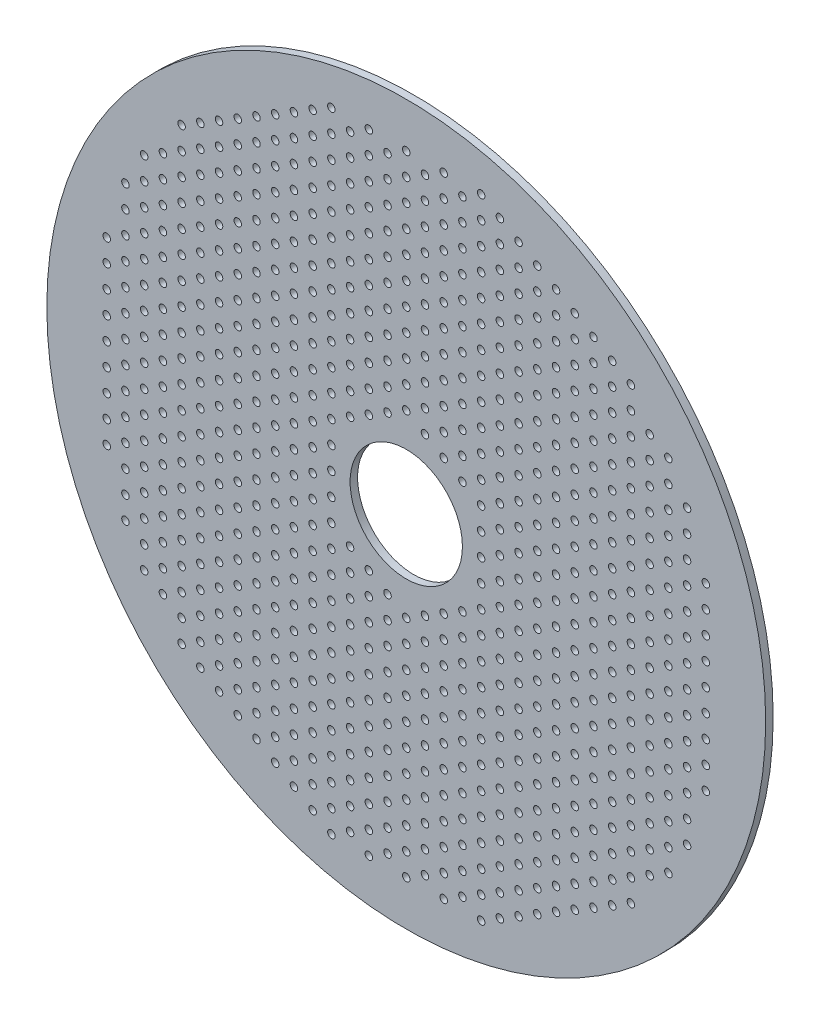
SolidWorks part; units mm, degrees
ref_plane "前视基准面" through (0, 0, 0) normal (0, 0, 1) x (1, 0, 0)
ref_plane "上视基准面" through (0, 0, 0) normal (0, 1, 0) x (1, 0, 0)
ref_plane "右视基准面" through (0, 0, 0) normal (1, 0, 0) x (0, 0, -1)
other "Configuration Table"
sketch "草图1" plane through (0, 0, 0) normal (0, 0, 1) x (1, 0, 0)
  line L0 (972.5716, 0) -> (-1078.2776, 0) construction
  line L1 (-52.853, -768.3582) -> (-52.853, 768.3582) construction
  line L2 (-452.853, 0) -> (-452.853, -30) construction
  line L3 (-202.853, 0) -> (-202.853, -30) construction
  line L4 (97.147, 0) -> (97.147, -30) construction
  line L5 (347.147, 0) -> (347.147, -30) construction
  circle A2 centre (-152.853, 0) radius 5
  circle A3 centre (-202.853, 0) radius 5
  circle A4 centre (-252.853, 0) radius 5
  circle A5 centre (-302.853, 0) radius 5
  circle A6 centre (-352.853, 0) radius 5
  circle A7 centre (-402.853, 0) radius 5
  circle A8 centre (-452.853, 0) radius 5
  circle A9 centre (-452.853, -30) radius 5
  circle A10 centre (-452.853, -60) radius 5
  circle A11 centre (-452.853, -90) radius 5
  circle A12 centre (-452.853, -120) radius 5
  circle A13 centre (-402.853, -30) radius 5
  circle A14 centre (-402.853, -60) radius 5
  circle A15 centre (-402.853, -90) radius 5
  circle A16 centre (-402.853, -120) radius 5
  circle A17 centre (-402.853, -150) radius 5
  circle A18 centre (-402.853, -180) radius 5
  circle A19 centre (-402.853, -210) radius 5
  circle A20 centre (-402.853, -240) radius 5
  circle A21 centre (-352.853, -30) radius 5
  circle A22 centre (-352.853, -60) radius 5
  circle A23 centre (-352.853, -90) radius 5
  circle A24 centre (-352.853, -120) radius 5
  circle A25 centre (-352.853, -150) radius 5
  circle A26 centre (-352.853, -180) radius 5
  circle A27 centre (-352.853, -210) radius 5
  circle A28 centre (-352.853, -240) radius 5
  circle A29 centre (-352.853, -270) radius 5
  circle A30 centre (-352.853, -300) radius 5
  circle A31 centre (-302.853, -30) radius 5
  circle A32 centre (-302.853, -60) radius 5
  circle A33 centre (-302.853, -90) radius 5
  circle A34 centre (-302.853, -120) radius 5
  circle A35 centre (-302.853, -150) radius 5
  circle A36 centre (-302.853, -180) radius 5
  circle A37 centre (-302.853, -210) radius 5
  circle A38 centre (-302.853, -240) radius 5
  circle A39 centre (-302.853, -270) radius 5
  circle A40 centre (-302.853, -300) radius 5
  circle A41 centre (-302.853, -330) radius 5
  circle A42 centre (-252.853, -30) radius 5
  circle A43 centre (-252.853, -60) radius 5
  circle A44 centre (-252.853, -90) radius 5
  circle A45 centre (-252.853, -120) radius 5
  circle A46 centre (-252.853, -150) radius 5
  circle A47 centre (-252.853, -180) radius 5
  circle A48 centre (-252.853, -210) radius 5
  circle A49 centre (-252.853, -240) radius 5
  circle A50 centre (-252.853, -270) radius 5
  circle A51 centre (-252.853, -300) radius 5
  circle A52 centre (-252.853, -330) radius 5
  circle A53 centre (-252.853, -360) radius 5
  circle A54 centre (-202.853, -30) radius 5
  circle A55 centre (-202.853, -60) radius 5
  circle A56 centre (-202.853, -90) radius 5
  circle A57 centre (-202.853, -120) radius 5
  circle A58 centre (-202.853, -150) radius 5
  circle A59 centre (-202.853, -180) radius 5
  circle A60 centre (-202.853, -210) radius 5
  circle A61 centre (-202.853, -240) radius 5
  circle A62 centre (-202.853, -270) radius 5
  circle A63 centre (-202.853, -300) radius 5
  circle A64 centre (-202.853, -330) radius 5
  circle A65 centre (-202.853, -360) radius 5
  circle A66 centre (-202.853, -390) radius 5
  circle A67 centre (-152.853, -30) radius 5
  circle A68 centre (-152.853, -60) radius 5
  circle A69 centre (-152.853, -90) radius 5
  circle A70 centre (-152.853, -120) radius 5
  circle A71 centre (-152.853, -150) radius 5
  circle A72 centre (-152.853, -180) radius 5
  circle A73 centre (-152.853, -210) radius 5
  circle A74 centre (-152.853, -240) radius 5
  circle A75 centre (-152.853, -270) radius 5
  circle A76 centre (-152.853, -300) radius 5
  circle A77 centre (-152.853, -330) radius 5
  circle A78 centre (-152.853, -360) radius 5
  circle A79 centre (-152.853, -390) radius 5
  circle A80 centre (-152.853, -420) radius 5
  circle A81 centre (-427.853, -15) radius 5
  circle A82 centre (-377.853, -15) radius 5
  circle A83 centre (-327.853, -15) radius 5
  circle A84 centre (-277.853, -15) radius 5
  circle A85 centre (-227.853, -15) radius 5
  circle A86 centre (-177.853, -15) radius 5
  circle A87 centre (-377.853, -45) radius 5
  circle A88 centre (-327.853, -45) radius 5
  circle A89 centre (-277.853, -45) radius 5
  circle A90 centre (-227.853, -45) radius 5
  circle A91 centre (-177.853, -45) radius 5
  circle A92 centre (-377.853, -75) radius 5
  circle A93 centre (-327.853, -75) radius 5
  circle A94 centre (-277.853, -75) radius 5
  circle A95 centre (-227.853, -75) radius 5
  circle A96 centre (-177.853, -75) radius 5
  circle A97 centre (-377.853, -105) radius 5
  circle A98 centre (-327.853, -105) radius 5
  circle A99 centre (-277.853, -105) radius 5
  circle A100 centre (-227.853, -105) radius 5
  circle A101 centre (-177.853, -105) radius 5
  circle A102 centre (-377.853, -135) radius 5
  circle A103 centre (-327.853, -135) radius 5
  circle A104 centre (-277.853, -135) radius 5
  circle A105 centre (-227.853, -135) radius 5
  circle A106 centre (-177.853, -135) radius 5
  circle A107 centre (-377.853, -165) radius 5
  circle A108 centre (-327.853, -165) radius 5
  circle A109 centre (-277.853, -165) radius 5
  circle A110 centre (-227.853, -165) radius 5
  circle A111 centre (-177.853, -165) radius 5
  circle A112 centre (-377.853, -195) radius 5
  circle A113 centre (-327.853, -195) radius 5
  circle A114 centre (-277.853, -195) radius 5
  circle A115 centre (-227.853, -195) radius 5
  circle A116 centre (-177.853, -195) radius 5
  circle A117 centre (-377.853, -225) radius 5
  circle A118 centre (-327.853, -225) radius 5
  circle A119 centre (-277.853, -225) radius 5
  circle A120 centre (-227.853, -225) radius 5
  circle A121 centre (-177.853, -225) radius 5
  circle A122 centre (-377.853, -255) radius 5
  circle A123 centre (-327.853, -255) radius 5
  circle A124 centre (-277.853, -255) radius 5
  circle A125 centre (-227.853, -255) radius 5
  circle A126 centre (-177.853, -255) radius 5
  circle A128 centre (-327.853, -285) radius 5
  circle A129 centre (-277.853, -285) radius 5
  circle A130 centre (-227.853, -285) radius 5
  circle A131 centre (-177.853, -285) radius 5
  circle A133 centre (-327.853, -315) radius 5
  circle A134 centre (-277.853, -315) radius 5
  circle A135 centre (-227.853, -315) radius 5
  circle A136 centre (-177.853, -315) radius 5
  circle A139 centre (-277.853, -345) radius 5
  circle A140 centre (-227.853, -345) radius 5
  circle A141 centre (-177.853, -345) radius 5
  circle A145 centre (-227.853, -375) radius 5
  circle A146 centre (-177.853, -375) radius 5
  circle A151 centre (-177.853, -405) radius 5
  circle A167 centre (-427.853, -45) radius 5
  circle A168 centre (-427.853, -75) radius 5
  circle A169 centre (-427.853, -105) radius 5
  circle A170 centre (-427.853, -135) radius 5
  circle A171 centre (-427.853, -165) radius 5
  circle A172 centre (-427.853, -195) radius 5
  circle A183 centre (-427.853, -255) radius 5 [skipped]
  circle A184 centre (-427.853, -285) radius 5 [skipped]
  circle A185 centre (-427.853, -315) radius 5 [skipped]
  circle A186 centre (-427.853, -345) radius 5 [skipped]
  circle A187 centre (-427.853, -375) radius 5 [skipped]
  circle A188 centre (-427.853, -405) radius 5 [skipped]
  circle A189 centre (-427.853, -435) radius 5 [skipped]
  circle A190 centre (-427.853, -465) radius 5 [skipped]
  circle A191 centre (-427.853, -495) radius 5 [skipped]
  circle A192 centre (-427.853, -225) radius 5 [skipped]
  circle A193 centre (-377.853, -465) radius 5 [skipped]
  circle A194 centre (-327.853, -465) radius 5 [skipped]
  circle A195 centre (-277.853, -465) radius 5 [skipped]
  circle A196 centre (-227.853, -465) radius 5 [skipped]
  circle A197 centre (-177.853, -465) radius 5 [skipped]
  circle A198 centre (-377.853, -495) radius 5 [skipped]
  circle A199 centre (-327.853, -495) radius 5 [skipped]
  circle A200 centre (-277.853, -495) radius 5 [skipped]
  circle A201 centre (-227.853, -495) radius 5 [skipped]
  circle A202 centre (-177.853, -495) radius 5 [skipped]
  circle A203 centre (-377.853, -375) radius 5 [skipped]
  circle A204 centre (-327.853, -375) radius 5 [skipped]
  circle A205 centre (-377.853, -405) radius 5 [skipped]
  circle A206 centre (-327.853, -405) radius 5 [skipped]
  circle A207 centre (-377.853, -435) radius 5 [skipped]
  circle A208 centre (-327.853, -435) radius 5 [skipped]
  circle A209 centre (-277.853, -405) radius 5 [skipped]
  circle A210 centre (-277.853, -435) radius 5 [skipped]
  circle A211 centre (-377.853, -345) radius 5 [skipped]
  circle A212 centre (-377.853, -315) radius 5 [skipped]
  circle A213 centre (-227.853, -435) radius 5 [skipped]
  circle A214 centre (-327.853, -345) radius 5 [skipped]
  circle A215 centre (-277.853, -375) radius 5 [skipped]
  circle A216 centre (-227.853, -405) radius 5 [skipped]
  circle A217 centre (-177.853, -435) radius 5 [skipped]
  circle A218 centre (-377.853, -285) radius 5 [skipped]
  circle A233 centre (-77.853, -105) radius 5
  circle A237 centre (-77.853, -135) radius 5
  circle A238 centre (-52.853, -120) radius 5
  circle A241 centre (-77.853, -165) radius 5
  circle A242 centre (-52.853, -150) radius 5
  circle A245 centre (-77.853, -195) radius 5
  circle A246 centre (-52.853, -180) radius 5
  circle A249 centre (-77.853, -225) radius 5
  circle A250 centre (-52.853, -210) radius 5
  circle A253 centre (-77.853, -255) radius 5
  circle A254 centre (-52.853, -240) radius 5
  circle A257 centre (-77.853, -285) radius 5
  circle A258 centre (-52.853, -270) radius 5
  circle A261 centre (-77.853, -315) radius 5
  circle A262 centre (-52.853, -300) radius 5
  circle A265 centre (-77.853, -345) radius 5
  circle A266 centre (-52.853, -330) radius 5
  circle A269 centre (-77.853, -375) radius 5
  circle A270 centre (-52.853, -360) radius 5
  circle A273 centre (-77.853, -405) radius 5
  circle A274 centre (-52.853, -390) radius 5
  circle A278 centre (-52.853, -420) radius 5
  circle A303 centre (-127.853, -75) radius 5
  circle A305 centre (-127.853, -105) radius 5
  circle A306 centre (-102.853, -90) radius 5
  circle A307 centre (-127.853, -135) radius 5
  circle A308 centre (-102.853, -120) radius 5
  circle A309 centre (-127.853, -165) radius 5
  circle A310 centre (-102.853, -150) radius 5
  circle A311 centre (-127.853, -195) radius 5
  circle A312 centre (-102.853, -180) radius 5
  circle A313 centre (-127.853, -225) radius 5
  circle A314 centre (-102.853, -210) radius 5
  circle A315 centre (-127.853, -255) radius 5
  circle A316 centre (-102.853, -240) radius 5
  circle A317 centre (-127.853, -285) radius 5
  circle A318 centre (-102.853, -270) radius 5
  circle A319 centre (-127.853, -315) radius 5
  circle A320 centre (-102.853, -300) radius 5
  circle A321 centre (-127.853, -345) radius 5
  circle A322 centre (-102.853, -330) radius 5
  circle A323 centre (-127.853, -375) radius 5
  circle A324 centre (-102.853, -360) radius 5
  circle A325 centre (-127.853, -405) radius 5
  circle A326 centre (-102.853, -390) radius 5
  circle A328 centre (-102.853, -420) radius 5
  circle A339 centre (-52.853, 0) radius 75
  circle A370 centre (-2.853, -420) radius 5
  circle A378 centre (-2.853, -390) radius 5
  circle A379 centre (22.147, -405) radius 5
  circle A380 centre (-2.853, -360) radius 5
  circle A381 centre (22.147, -375) radius 5
  circle A382 centre (-2.853, -330) radius 5
  circle A383 centre (22.147, -345) radius 5
  circle A384 centre (-2.853, -300) radius 5
  circle A385 centre (22.147, -315) radius 5
  circle A386 centre (-2.853, -270) radius 5
  circle A387 centre (22.147, -285) radius 5
  circle A388 centre (-2.853, -240) radius 5
  circle A389 centre (22.147, -255) radius 5
  circle A390 centre (-2.853, -210) radius 5
  circle A391 centre (22.147, -225) radius 5
  circle A392 centre (-2.853, -180) radius 5
  circle A393 centre (22.147, -195) radius 5
  circle A394 centre (-2.853, -150) radius 5
  circle A395 centre (22.147, -165) radius 5
  circle A396 centre (-2.853, -120) radius 5
  circle A397 centre (22.147, -135) radius 5
  circle A398 centre (-2.853, -90) radius 5
  circle A399 centre (22.147, -105) radius 5
  circle A400 centre (22.147, -75) radius 5
  circle A401 centre (-27.853, -405) radius 5
  circle A402 centre (-27.853, -375) radius 5
  circle A403 centre (-27.853, -345) radius 5
  circle A404 centre (-27.853, -315) radius 5
  circle A405 centre (-27.853, -285) radius 5
  circle A406 centre (-27.853, -255) radius 5
  circle A407 centre (-27.853, -225) radius 5
  circle A408 centre (-27.853, -195) radius 5
  circle A409 centre (-27.853, -165) radius 5
  circle A410 centre (-27.853, -135) radius 5
  circle A411 centre (-27.853, -105) radius 5
  circle A412 centre (322.147, -195) radius 5
  circle A413 centre (322.147, -165) radius 5
  circle A414 centre (322.147, -135) radius 5
  circle A415 centre (322.147, -105) radius 5
  circle A416 centre (322.147, -75) radius 5
  circle A417 centre (322.147, -45) radius 5
  circle A418 centre (72.147, -405) radius 5
  circle A419 centre (72.147, -375) radius 5
  circle A420 centre (122.147, -375) radius 5
  circle A421 centre (72.147, -345) radius 5
  circle A422 centre (122.147, -345) radius 5
  circle A423 centre (172.147, -345) radius 5
  circle A424 centre (72.147, -315) radius 5
  circle A425 centre (122.147, -315) radius 5
  circle A426 centre (172.147, -315) radius 5
  circle A427 centre (222.147, -315) radius 5
  circle A428 centre (72.147, -285) radius 5
  circle A429 centre (122.147, -285) radius 5
  circle A430 centre (172.147, -285) radius 5
  circle A431 centre (222.147, -285) radius 5
  circle A432 centre (72.147, -255) radius 5
  circle A433 centre (122.147, -255) radius 5
  circle A434 centre (172.147, -255) radius 5
  circle A435 centre (222.147, -255) radius 5
  circle A436 centre (272.147, -255) radius 5
  circle A437 centre (72.147, -225) radius 5
  circle A438 centre (122.147, -225) radius 5
  circle A439 centre (172.147, -225) radius 5
  circle A440 centre (222.147, -225) radius 5
  circle A441 centre (272.147, -225) radius 5
  circle A442 centre (72.147, -195) radius 5
  circle A443 centre (122.147, -195) radius 5
  circle A444 centre (172.147, -195) radius 5
  circle A445 centre (222.147, -195) radius 5
  circle A446 centre (272.147, -195) radius 5
  circle A447 centre (72.147, -165) radius 5
  circle A448 centre (122.147, -165) radius 5
  circle A449 centre (172.147, -165) radius 5
  circle A450 centre (222.147, -165) radius 5
  circle A451 centre (272.147, -165) radius 5
  circle A452 centre (72.147, -135) radius 5
  circle A453 centre (122.147, -135) radius 5
  circle A454 centre (172.147, -135) radius 5
  circle A455 centre (222.147, -135) radius 5
  circle A456 centre (272.147, -135) radius 5
  circle A457 centre (72.147, -105) radius 5
  circle A458 centre (122.147, -105) radius 5
  circle A459 centre (172.147, -105) radius 5
  circle A460 centre (222.147, -105) radius 5
  circle A461 centre (272.147, -105) radius 5
  circle A462 centre (72.147, -75) radius 5
  circle A463 centre (122.147, -75) radius 5
  circle A464 centre (172.147, -75) radius 5
  circle A465 centre (222.147, -75) radius 5
  circle A466 centre (272.147, -75) radius 5
  circle A467 centre (72.147, -45) radius 5
  circle A468 centre (122.147, -45) radius 5
  circle A469 centre (172.147, -45) radius 5
  circle A470 centre (222.147, -45) radius 5
  circle A471 centre (272.147, -45) radius 5
  circle A472 centre (72.147, -15) radius 5
  circle A473 centre (122.147, -15) radius 5
  circle A474 centre (172.147, -15) radius 5
  circle A475 centre (222.147, -15) radius 5
  circle A476 centre (272.147, -15) radius 5
  circle A477 centre (322.147, -15) radius 5
  circle A478 centre (47.147, -420) radius 5
  circle A479 centre (47.147, -390) radius 5
  circle A480 centre (47.147, -360) radius 5
  circle A481 centre (47.147, -330) radius 5
  circle A482 centre (47.147, -300) radius 5
  circle A483 centre (47.147, -270) radius 5
  circle A484 centre (47.147, -240) radius 5
  circle A485 centre (47.147, -210) radius 5
  circle A486 centre (47.147, -180) radius 5
  circle A487 centre (47.147, -150) radius 5
  circle A488 centre (47.147, -120) radius 5
  circle A489 centre (47.147, -90) radius 5
  circle A490 centre (47.147, -60) radius 5
  circle A491 centre (47.147, -30) radius 5
  circle A492 centre (97.147, -390) radius 5
  circle A493 centre (97.147, -360) radius 5
  circle A494 centre (97.147, -330) radius 5
  circle A495 centre (97.147, -300) radius 5
  circle A496 centre (97.147, -270) radius 5
  circle A497 centre (97.147, -240) radius 5
  circle A498 centre (97.147, -210) radius 5
  circle A499 centre (97.147, -180) radius 5
  circle A500 centre (97.147, -150) radius 5
  circle A501 centre (97.147, -120) radius 5
  circle A502 centre (97.147, -90) radius 5
  circle A503 centre (97.147, -60) radius 5
  circle A504 centre (97.147, -30) radius 5
  circle A505 centre (147.147, -360) radius 5
  circle A506 centre (147.147, -330) radius 5
  circle A507 centre (147.147, -300) radius 5
  circle A508 centre (147.147, -270) radius 5
  circle A509 centre (147.147, -240) radius 5
  circle A510 centre (147.147, -210) radius 5
  circle A511 centre (147.147, -180) radius 5
  circle A512 centre (147.147, -150) radius 5
  circle A513 centre (147.147, -120) radius 5
  circle A514 centre (147.147, -90) radius 5
  circle A515 centre (147.147, -60) radius 5
  circle A516 centre (147.147, -30) radius 5
  circle A517 centre (197.147, -330) radius 5
  circle A518 centre (197.147, -300) radius 5
  circle A519 centre (197.147, -270) radius 5
  circle A520 centre (197.147, -240) radius 5
  circle A521 centre (197.147, -210) radius 5
  circle A522 centre (197.147, -180) radius 5
  circle A523 centre (197.147, -150) radius 5
  circle A524 centre (197.147, -120) radius 5
  circle A525 centre (197.147, -90) radius 5
  circle A526 centre (197.147, -60) radius 5
  circle A527 centre (197.147, -30) radius 5
  circle A528 centre (247.147, -300) radius 5
  circle A529 centre (247.147, -270) radius 5
  circle A530 centre (247.147, -240) radius 5
  circle A531 centre (247.147, -210) radius 5
  circle A532 centre (247.147, -180) radius 5
  circle A533 centre (247.147, -150) radius 5
  circle A534 centre (247.147, -120) radius 5
  circle A535 centre (247.147, -90) radius 5
  circle A536 centre (247.147, -60) radius 5
  circle A537 centre (247.147, -30) radius 5
  circle A538 centre (297.147, -240) radius 5
  circle A539 centre (297.147, -210) radius 5
  circle A540 centre (297.147, -180) radius 5
  circle A541 centre (297.147, -150) radius 5
  circle A542 centre (297.147, -120) radius 5
  circle A543 centre (297.147, -90) radius 5
  circle A544 centre (297.147, -60) radius 5
  circle A545 centre (297.147, -30) radius 5
  circle A546 centre (347.147, -120) radius 5
  circle A547 centre (347.147, -90) radius 5
  circle A548 centre (347.147, -60) radius 5
  circle A549 centre (347.147, -30) radius 5
  circle A550 centre (347.147, 0) radius 5
  circle A551 centre (297.147, 0) radius 5
  circle A552 centre (247.147, 0) radius 5
  circle A553 centre (197.147, 0) radius 5
  circle A554 centre (147.147, 0) radius 5
  circle A555 centre (97.147, 0) radius 5
  circle A556 centre (47.147, 0) radius 5
  circle A557 centre (347.147, 30) radius 5
  circle A558 centre (347.147, 60) radius 5
  circle A559 centre (347.147, 90) radius 5
  circle A560 centre (347.147, 120) radius 5
  circle A561 centre (297.147, 30) radius 5
  circle A562 centre (297.147, 60) radius 5
  circle A563 centre (297.147, 90) radius 5
  circle A564 centre (297.147, 120) radius 5
  circle A565 centre (297.147, 150) radius 5
  circle A566 centre (297.147, 180) radius 5
  circle A567 centre (297.147, 210) radius 5
  circle A568 centre (297.147, 240) radius 5
  circle A569 centre (247.147, 30) radius 5
  circle A570 centre (247.147, 60) radius 5
  circle A571 centre (247.147, 90) radius 5
  circle A572 centre (247.147, 120) radius 5
  circle A573 centre (247.147, 150) radius 5
  circle A574 centre (247.147, 180) radius 5
  circle A575 centre (247.147, 210) radius 5
  circle A576 centre (247.147, 240) radius 5
  circle A577 centre (247.147, 270) radius 5
  circle A578 centre (247.147, 300) radius 5
  circle A579 centre (197.147, 30) radius 5
  circle A580 centre (197.147, 60) radius 5
  circle A581 centre (197.147, 90) radius 5
  circle A582 centre (197.147, 120) radius 5
  circle A583 centre (197.147, 150) radius 5
  circle A584 centre (197.147, 180) radius 5
  circle A585 centre (197.147, 210) radius 5
  circle A586 centre (197.147, 240) radius 5
  circle A587 centre (197.147, 270) radius 5
  circle A588 centre (197.147, 300) radius 5
  circle A589 centre (197.147, 330) radius 5
  circle A590 centre (147.147, 30) radius 5
  circle A591 centre (147.147, 60) radius 5
  circle A592 centre (147.147, 90) radius 5
  circle A593 centre (147.147, 120) radius 5
  circle A594 centre (147.147, 150) radius 5
  circle A595 centre (147.147, 180) radius 5
  circle A596 centre (147.147, 210) radius 5
  circle A597 centre (147.147, 240) radius 5
  circle A598 centre (147.147, 270) radius 5
  circle A599 centre (147.147, 300) radius 5
  circle A600 centre (147.147, 330) radius 5
  circle A601 centre (147.147, 360) radius 5
  circle A602 centre (97.147, 30) radius 5
  circle A603 centre (97.147, 60) radius 5
  circle A604 centre (97.147, 90) radius 5
  circle A605 centre (97.147, 120) radius 5
  circle A606 centre (97.147, 150) radius 5
  circle A607 centre (97.147, 180) radius 5
  circle A608 centre (97.147, 210) radius 5
  circle A609 centre (97.147, 240) radius 5
  circle A610 centre (97.147, 270) radius 5
  circle A611 centre (97.147, 300) radius 5
  circle A612 centre (97.147, 330) radius 5
  circle A613 centre (97.147, 360) radius 5
  circle A614 centre (97.147, 390) radius 5
  circle A615 centre (47.147, 30) radius 5
  circle A616 centre (47.147, 60) radius 5
  circle A617 centre (47.147, 90) radius 5
  circle A618 centre (47.147, 120) radius 5
  circle A619 centre (47.147, 150) radius 5
  circle A620 centre (47.147, 180) radius 5
  circle A621 centre (47.147, 210) radius 5
  circle A622 centre (47.147, 240) radius 5
  circle A623 centre (47.147, 270) radius 5
  circle A624 centre (47.147, 300) radius 5
  circle A625 centre (47.147, 330) radius 5
  circle A626 centre (47.147, 360) radius 5
  circle A627 centre (47.147, 390) radius 5
  circle A628 centre (47.147, 420) radius 5
  circle A629 centre (322.147, 15) radius 5
  circle A630 centre (272.147, 15) radius 5
  circle A631 centre (222.147, 15) radius 5
  circle A632 centre (172.147, 15) radius 5
  circle A633 centre (122.147, 15) radius 5
  circle A634 centre (72.147, 15) radius 5
  circle A635 centre (272.147, 45) radius 5
  circle A636 centre (222.147, 45) radius 5
  circle A637 centre (172.147, 45) radius 5
  circle A638 centre (122.147, 45) radius 5
  circle A639 centre (72.147, 45) radius 5
  circle A640 centre (272.147, 75) radius 5
  circle A641 centre (222.147, 75) radius 5
  circle A642 centre (172.147, 75) radius 5
  circle A643 centre (122.147, 75) radius 5
  circle A644 centre (72.147, 75) radius 5
  circle A645 centre (272.147, 105) radius 5
  circle A646 centre (222.147, 105) radius 5
  circle A647 centre (172.147, 105) radius 5
  circle A648 centre (122.147, 105) radius 5
  circle A649 centre (72.147, 105) radius 5
  circle A650 centre (272.147, 135) radius 5
  circle A651 centre (222.147, 135) radius 5
  circle A652 centre (172.147, 135) radius 5
  circle A653 centre (122.147, 135) radius 5
  circle A654 centre (72.147, 135) radius 5
  circle A655 centre (272.147, 165) radius 5
  circle A656 centre (222.147, 165) radius 5
  circle A657 centre (172.147, 165) radius 5
  circle A658 centre (122.147, 165) radius 5
  circle A659 centre (72.147, 165) radius 5
  circle A660 centre (272.147, 195) radius 5
  circle A661 centre (222.147, 195) radius 5
  circle A662 centre (172.147, 195) radius 5
  circle A663 centre (122.147, 195) radius 5
  circle A664 centre (72.147, 195) radius 5
  circle A665 centre (272.147, 225) radius 5
  circle A666 centre (222.147, 225) radius 5
  circle A667 centre (172.147, 225) radius 5
  circle A668 centre (122.147, 225) radius 5
  circle A669 centre (72.147, 225) radius 5
  circle A670 centre (272.147, 255) radius 5
  circle A671 centre (222.147, 255) radius 5
  circle A672 centre (172.147, 255) radius 5
  circle A673 centre (122.147, 255) radius 5
  circle A674 centre (72.147, 255) radius 5
  circle A675 centre (222.147, 285) radius 5
  circle A676 centre (172.147, 285) radius 5
  circle A677 centre (122.147, 285) radius 5
  circle A678 centre (72.147, 285) radius 5
  circle A679 centre (222.147, 315) radius 5
  circle A680 centre (172.147, 315) radius 5
  circle A681 centre (122.147, 315) radius 5
  circle A682 centre (72.147, 315) radius 5
  circle A683 centre (172.147, 345) radius 5
  circle A684 centre (122.147, 345) radius 5
  circle A685 centre (72.147, 345) radius 5
  circle A686 centre (122.147, 375) radius 5
  circle A687 centre (72.147, 375) radius 5
  circle A688 centre (72.147, 405) radius 5
  circle A689 centre (322.147, 45) radius 5
  circle A690 centre (322.147, 75) radius 5
  circle A691 centre (322.147, 105) radius 5
  circle A692 centre (322.147, 135) radius 5
  circle A693 centre (322.147, 165) radius 5
  circle A694 centre (322.147, 195) radius 5
  circle A695 centre (-27.853, 105) radius 5
  circle A696 centre (-27.853, 135) radius 5
  circle A697 centre (-27.853, 165) radius 5
  circle A698 centre (-27.853, 195) radius 5
  circle A699 centre (-27.853, 225) radius 5
  circle A700 centre (-27.853, 255) radius 5
  circle A701 centre (-27.853, 285) radius 5
  circle A702 centre (-27.853, 315) radius 5
  circle A703 centre (-27.853, 345) radius 5
  circle A704 centre (-27.853, 375) radius 5
  circle A705 centre (-27.853, 405) radius 5
  circle A706 centre (22.147, 75) radius 5
  circle A707 centre (22.147, 105) radius 5
  circle A708 centre (-2.853, 90) radius 5
  circle A709 centre (22.147, 135) radius 5
  circle A710 centre (-2.853, 120) radius 5
  circle A711 centre (22.147, 165) radius 5
  circle A712 centre (-2.853, 150) radius 5
  circle A713 centre (22.147, 195) radius 5
  circle A714 centre (-2.853, 180) radius 5
  circle A715 centre (22.147, 225) radius 5
  circle A716 centre (-2.853, 210) radius 5
  circle A717 centre (22.147, 255) radius 5
  circle A718 centre (-2.853, 240) radius 5
  circle A719 centre (22.147, 285) radius 5
  circle A720 centre (-2.853, 270) radius 5
  circle A721 centre (22.147, 315) radius 5
  circle A722 centre (-2.853, 300) radius 5
  circle A723 centre (22.147, 345) radius 5
  circle A724 centre (-2.853, 330) radius 5
  circle A725 centre (22.147, 375) radius 5
  circle A726 centre (-2.853, 360) radius 5
  circle A727 centre (22.147, 405) radius 5
  circle A728 centre (-2.853, 390) radius 5
  circle A729 centre (-2.853, 420) radius 5
  circle A730 centre (-102.853, 420) radius 5
  circle A731 centre (-102.853, 390) radius 5
  circle A732 centre (-127.853, 405) radius 5
  circle A733 centre (-102.853, 360) radius 5
  circle A734 centre (-127.853, 375) radius 5
  circle A735 centre (-102.853, 330) radius 5
  circle A736 centre (-127.853, 345) radius 5
  circle A737 centre (-102.853, 300) radius 5
  circle A738 centre (-127.853, 315) radius 5
  circle A739 centre (-102.853, 270) radius 5
  circle A740 centre (-127.853, 285) radius 5
  circle A741 centre (-102.853, 240) radius 5
  circle A742 centre (-127.853, 255) radius 5
  circle A743 centre (-102.853, 210) radius 5
  circle A744 centre (-127.853, 225) radius 5
  circle A745 centre (-102.853, 180) radius 5
  circle A746 centre (-127.853, 195) radius 5
  circle A747 centre (-102.853, 150) radius 5
  circle A748 centre (-127.853, 165) radius 5
  circle A749 centre (-102.853, 120) radius 5
  circle A750 centre (-127.853, 135) radius 5
  circle A751 centre (-102.853, 90) radius 5
  circle A752 centre (-127.853, 105) radius 5
  circle A753 centre (-127.853, 75) radius 5
  circle A754 centre (-52.853, 420) radius 5
  circle A755 centre (-52.853, 390) radius 5
  circle A756 centre (-77.853, 405) radius 5
  circle A757 centre (-52.853, 360) radius 5
  circle A758 centre (-77.853, 375) radius 5
  circle A759 centre (-52.853, 330) radius 5
  circle A760 centre (-77.853, 345) radius 5
  circle A761 centre (-52.853, 300) radius 5
  circle A762 centre (-77.853, 315) radius 5
  circle A763 centre (-52.853, 270) radius 5
  circle A764 centre (-77.853, 285) radius 5
  circle A765 centre (-52.853, 240) radius 5
  circle A766 centre (-77.853, 255) radius 5
  circle A767 centre (-52.853, 210) radius 5
  circle A768 centre (-77.853, 225) radius 5
  circle A769 centre (-52.853, 180) radius 5
  circle A770 centre (-77.853, 195) radius 5
  circle A771 centre (-52.853, 150) radius 5
  circle A772 centre (-77.853, 165) radius 5
  circle A773 centre (-52.853, 120) radius 5
  circle A774 centre (-77.853, 135) radius 5
  circle A775 centre (-77.853, 105) radius 5
  circle A776 centre (-427.853, 195) radius 5
  circle A777 centre (-427.853, 165) radius 5
  circle A778 centre (-427.853, 135) radius 5
  circle A779 centre (-427.853, 105) radius 5
  circle A780 centre (-427.853, 75) radius 5
  circle A781 centre (-427.853, 45) radius 5
  circle A782 centre (-177.853, 405) radius 5
  circle A783 centre (-177.853, 375) radius 5
  circle A784 centre (-227.853, 375) radius 5
  circle A785 centre (-177.853, 345) radius 5
  circle A786 centre (-227.853, 345) radius 5
  circle A787 centre (-277.853, 345) radius 5
  circle A788 centre (-177.853, 315) radius 5
  circle A789 centre (-227.853, 315) radius 5
  circle A790 centre (-277.853, 315) radius 5
  circle A791 centre (-327.853, 315) radius 5
  circle A792 centre (-177.853, 285) radius 5
  circle A793 centre (-227.853, 285) radius 5
  circle A794 centre (-277.853, 285) radius 5
  circle A795 centre (-327.853, 285) radius 5
  circle A796 centre (-177.853, 255) radius 5
  circle A797 centre (-227.853, 255) radius 5
  circle A798 centre (-277.853, 255) radius 5
  circle A799 centre (-327.853, 255) radius 5
  circle A800 centre (-377.853, 255) radius 5
  circle A801 centre (-177.853, 225) radius 5
  circle A802 centre (-227.853, 225) radius 5
  circle A803 centre (-277.853, 225) radius 5
  circle A804 centre (-327.853, 225) radius 5
  circle A805 centre (-377.853, 225) radius 5
  circle A806 centre (-177.853, 195) radius 5
  circle A807 centre (-227.853, 195) radius 5
  circle A808 centre (-277.853, 195) radius 5
  circle A809 centre (-327.853, 195) radius 5
  circle A810 centre (-377.853, 195) radius 5
  circle A811 centre (-177.853, 165) radius 5
  circle A812 centre (-227.853, 165) radius 5
  circle A813 centre (-277.853, 165) radius 5
  circle A814 centre (-327.853, 165) radius 5
  circle A815 centre (-377.853, 165) radius 5
  circle A816 centre (-177.853, 135) radius 5
  circle A817 centre (-227.853, 135) radius 5
  circle A818 centre (-277.853, 135) radius 5
  circle A819 centre (-327.853, 135) radius 5
  circle A820 centre (-377.853, 135) radius 5
  circle A821 centre (-177.853, 105) radius 5
  circle A822 centre (-227.853, 105) radius 5
  circle A823 centre (-277.853, 105) radius 5
  circle A824 centre (-327.853, 105) radius 5
  circle A825 centre (-377.853, 105) radius 5
  circle A826 centre (-177.853, 75) radius 5
  circle A827 centre (-227.853, 75) radius 5
  circle A828 centre (-277.853, 75) radius 5
  circle A829 centre (-327.853, 75) radius 5
  circle A830 centre (-377.853, 75) radius 5
  circle A831 centre (-177.853, 45) radius 5
  circle A832 centre (-227.853, 45) radius 5
  circle A833 centre (-277.853, 45) radius 5
  circle A834 centre (-327.853, 45) radius 5
  circle A835 centre (-377.853, 45) radius 5
  circle A836 centre (-177.853, 15) radius 5
  circle A837 centre (-227.853, 15) radius 5
  circle A838 centre (-277.853, 15) radius 5
  circle A839 centre (-327.853, 15) radius 5
  circle A840 centre (-377.853, 15) radius 5
  circle A841 centre (-427.853, 15) radius 5
  circle A842 centre (-152.853, 420) radius 5
  circle A843 centre (-152.853, 390) radius 5
  circle A844 centre (-152.853, 360) radius 5
  circle A845 centre (-152.853, 330) radius 5
  circle A846 centre (-152.853, 300) radius 5
  circle A847 centre (-152.853, 270) radius 5
  circle A848 centre (-152.853, 240) radius 5
  circle A849 centre (-152.853, 210) radius 5
  circle A850 centre (-152.853, 180) radius 5
  circle A851 centre (-152.853, 150) radius 5
  circle A852 centre (-152.853, 120) radius 5
  circle A853 centre (-152.853, 90) radius 5
  circle A854 centre (-152.853, 60) radius 5
  circle A855 centre (-152.853, 30) radius 5
  circle A856 centre (-202.853, 390) radius 5
  circle A857 centre (-202.853, 360) radius 5
  circle A858 centre (-202.853, 330) radius 5
  circle A859 centre (-202.853, 300) radius 5
  circle A860 centre (-202.853, 270) radius 5
  circle A861 centre (-202.853, 240) radius 5
  circle A862 centre (-202.853, 210) radius 5
  circle A863 centre (-202.853, 180) radius 5
  circle A864 centre (-202.853, 150) radius 5
  circle A865 centre (-202.853, 120) radius 5
  circle A866 centre (-202.853, 90) radius 5
  circle A867 centre (-202.853, 60) radius 5
  circle A868 centre (-202.853, 30) radius 5
  circle A869 centre (-252.853, 360) radius 5
  circle A870 centre (-252.853, 330) radius 5
  circle A871 centre (-252.853, 300) radius 5
  circle A872 centre (-252.853, 270) radius 5
  circle A873 centre (-252.853, 240) radius 5
  circle A874 centre (-252.853, 210) radius 5
  circle A875 centre (-252.853, 180) radius 5
  circle A876 centre (-252.853, 150) radius 5
  circle A877 centre (-252.853, 120) radius 5
  circle A878 centre (-252.853, 90) radius 5
  circle A879 centre (-252.853, 60) radius 5
  circle A880 centre (-252.853, 30) radius 5
  circle A881 centre (-302.853, 330) radius 5
  circle A882 centre (-302.853, 300) radius 5
  circle A883 centre (-302.853, 270) radius 5
  circle A884 centre (-302.853, 240) radius 5
  circle A885 centre (-302.853, 210) radius 5
  circle A886 centre (-302.853, 180) radius 5
  circle A887 centre (-302.853, 150) radius 5
  circle A888 centre (-302.853, 120) radius 5
  circle A889 centre (-302.853, 90) radius 5
  circle A890 centre (-302.853, 60) radius 5
  circle A891 centre (-302.853, 30) radius 5
  circle A892 centre (-352.853, 300) radius 5
  circle A893 centre (-352.853, 270) radius 5
  circle A894 centre (-352.853, 240) radius 5
  circle A895 centre (-352.853, 210) radius 5
  circle A896 centre (-352.853, 180) radius 5
  circle A897 centre (-352.853, 150) radius 5
  circle A898 centre (-352.853, 120) radius 5
  circle A899 centre (-352.853, 90) radius 5
  circle A900 centre (-352.853, 60) radius 5
  circle A901 centre (-352.853, 30) radius 5
  circle A902 centre (-402.853, 240) radius 5
  circle A903 centre (-402.853, 210) radius 5
  circle A904 centre (-402.853, 180) radius 5
  circle A905 centre (-402.853, 150) radius 5
  circle A906 centre (-402.853, 120) radius 5
  circle A907 centre (-402.853, 90) radius 5
  circle A908 centre (-402.853, 60) radius 5
  circle A909 centre (-402.853, 30) radius 5
  circle A910 centre (-452.853, 120) radius 5
  circle A911 centre (-452.853, 90) radius 5
  circle A912 centre (-452.853, 60) radius 5
  circle A913 centre (-452.853, 30) radius 5
  circle A914 centre (-52.853, 0) radius 480
  point P6 (-52.853, 0)
  point P9 (-52.853, 0)
  dimension "D2" = 15
  dimension "D3" = 10
  dimension "D4" = 7
  dimension "D6" = 30
  dimension "D12" = 30
  dimension "D14" = 25
  dimension "D15" = 15
  dimension "D18" = 25
  dimension "D5" = 5
  dimension "D7" = 9
  dimension "D8" = 11
  dimension "D9" = 12
  dimension "D10" = 13
  dimension "D11" = 14
  dimension "D13" = 15
  dimension "D16" = 6
  dimension "D17" = 17
extrude "凸台-拉伸1" add sketch "草图1" along normal blind 10
